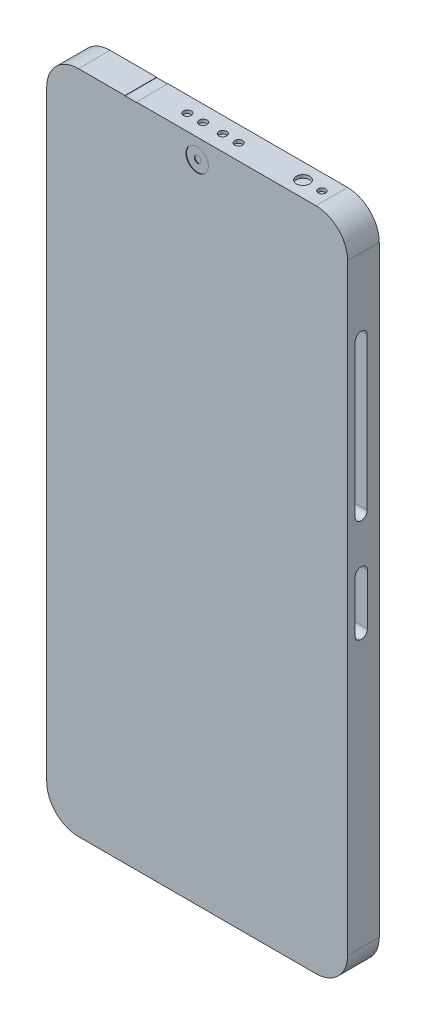
SolidWorks part; units mm, degrees
material "C (石墨)"
ref_plane "前视基准面" through (0, 0, 0) normal (0, 0, 1) x (1, 0, 0)
ref_plane "上视基准面" through (0, 0, 0) normal (0, 1, 0) x (1, 0, 0)
ref_plane "右视基准面" through (0, 0, 0) normal (1, 0, 0) x (0, 0, -1)
other "Configuration Table"
sketch "草图1" plane through (0, 0, 0) normal (0, 0, 1) x (1, 0, 0)
  line L1 (-37.5, 105) -> (37.5, 105)
  line L2 (-47.5, 95) -> (-47.5, -95)
  line L3 (-37.5, -105) -> (37.5, -105)
  line L4 (47.5, 95) -> (47.5, -95)
  line L5 (-47.5, 105) -> (47.5, -105) construction
  line L6 (-47.5, -105) -> (47.5, 105) construction
  arc A0 (-37.5, 105) -> (-47.5, 95) centre (-37.5, 95) ccw
  arc A1 (47.5, 95) -> (37.5, 105) centre (37.5, 95) ccw
  arc A2 (47.5, -95) -> (37.5, -105) centre (37.5, -95) cw
  arc A3 (-37.5, -105) -> (-47.5, -95) centre (-37.5, -95) cw
  point P0 (0, 0)
  dimension "D3" = 10
  dimension "D4" = 10
  dimension "D5" = 10
  dimension "D1" = 95
  dimension "D2" = 210
extrude "凸台-拉伸2" add sketch "草图1" along normal blind 10 contours A0 L2 A3 L3 A2 L4 A1 L1
sketch "草图8" plane through (0, 105, 0) normal (0, 1, 0) x (1, 0, 0)
  line L0 (0, -10) -> (0, 0) construction
  line L1 (-37.5, -10) -> (37.5, -10) construction
  line L3 (-37.5, 0) -> (37.5, 0) construction
  line L5 (-22.7874, 0) -> (-19.2126, 0)
  line L6 (-22.7874, 0) -> (-22.7874, -10)
  line L7 (-22.7874, -10) -> (-19.2126, -10)
  line L8 (-19.2126, 0) -> (-19.2126, -10)
  line L9 (22.7874, -10) -> (19.2126, -10)
  line L10 (19.2126, 0) -> (19.2126, -10)
  line L11 (22.7874, 0) -> (19.2126, 0)
  line L12 (22.7874, 0) -> (22.7874, -10)
  dimension "D2" = 42
  dimension "D1" = 3.5748
sketch "草图10" plane through (0, 105, 0) normal (0, 1, 0) x (1, 0, 0)
  line L0 (-37.5, -5) -> (37.5, -5) construction
  line L4 (0, 0) -> (0, -10) construction
  circle A0 centre (-3.1032, -5) radius 1.25
  circle A1 centre (-8.1032, -5) radius 1.25
  circle A2 centre (8.1032, -5) radius 1.25
  circle A3 centre (3.1032, -5) radius 1.25
  circle A4 centre (28.4294, -5) radius 2.1
  circle A5 centre (34.3689, -5) radius 1.15
  dimension "D2" = 2.5
  dimension "D3" = 4.2
  dimension "D4" = 2.3
  dimension "D1" = 2
sketch "草图12" plane through (0, 105, 0) normal (0, 1, 0) x (1, 0, 0)
extrude "切除-拉伸3" cut sketch "草图10" against normal blind 1 contours A4 | A2 | A3 | A0 | A1 | A5
sketch "草图14" plane through (0, -105, 0) normal (0, -1, 0) x (1, 0, 0)
  line L0 (-4.965, 4.9007) -> (4.835, 4.9007) construction
  line L1 (-4.965, 8.2769) -> (4.835, 8.2769)
  line L2 (-4.965, 1.5245) -> (4.835, 1.5245)
  arc A0 (-4.965, 8.2769) -> (-4.965, 1.5245) centre (-4.965, 4.9007) ccw
  arc A1 (4.835, 1.5245) -> (4.835, 8.2769) centre (4.835, 4.9007) ccw
  point P2 (-0.065, 4.9007)
  dimension "D1" = 3.3762
  dimension "D2" = 9.8
sketch "草图15" plane through (0, -105, 0) normal (0, -1, 0) x (1, 0, 0)
extrude "切除-拉伸4" cut sketch "草图14" against normal blind 20.0858 contours L2 A1 L1 A0
sketch "草图16" plane through (0, -105, 0) normal (0, -1, 0) x (1, 0, 0)
  line L0 (-35.02, 5.1655) -> (-20.02, 5.1655) construction
  line L1 (-35.02, 6.9529) -> (-20.02, 6.9529)
  line L2 (-35.02, 3.3781) -> (-20.02, 3.3781)
  arc A0 (-35.02, 6.9529) -> (-35.02, 3.3781) centre (-35.02, 5.1655) ccw
  arc A1 (-20.02, 3.3781) -> (-20.02, 6.9529) centre (-20.02, 5.1655) ccw
  circle A2 centre (-35.02, 5.1655) radius 0.55
  circle A3 centre (-14.9073, 5.1655) radius 1.45
  circle A4 centre (14.7296, 5.1655) radius 2.3283
  circle A5 centre (19.7296, 5.1655) radius 2.3283
  circle A6 centre (24.7296, 5.1655) radius 2.3283
  circle A7 centre (29.7296, 5.1655) radius 2.3283
  circle A8 centre (34.7296, 5.1655) radius 2.3283
  point P2 (-27.52, 5.1655)
  point P13 (-18.2326, 5.1655)
  dimension "D1" = 2.9
  dimension "D3" = 1.1
  dimension "D5" = 4.6566
  dimension "D2" = 15
  dimension "D6" = 3.3252
  dimension "D7" = 5
  dimension "D8" = 29.6369
  dimension "D4" = 5
extrude "切除-拉伸6" cut sketch "草图16" against normal blind 10 contours A4 | A3 | A8 | A7 | A6 | A5
sketch "草图18" plane through (0, -105, 0) normal (0, -1, 0) x (1, 0, 0)
  line L0 (-34.9782, 4.8823) -> (-19.8978, 4.8823) construction
  line L1 (-34.9782, 6.9263) -> (-19.8978, 6.9263)
  line L2 (-34.9782, 2.8383) -> (-19.8978, 2.8383)
  arc A0 (-34.9782, 6.9263) -> (-34.9782, 2.8383) centre (-34.9782, 4.8823) ccw
  arc A1 (-19.8978, 2.8383) -> (-19.8978, 6.9263) centre (-19.8978, 4.8823) ccw
  circle A2 centre (-34.9782, 4.8823) radius 0.5451
  point P2 (-27.438, 4.8823)
extrude "切除-拉伸7" cut sketch "草图18" against normal blind 10 contours A2
sketch "草图19" plane through (0, -105, 0) normal (0, -1, 0) x (1, 0, 0)
  line L0 (-34.9782, 4.8823) -> (-21.8321, 4.8823) construction
  line L1 (-34.9782, 7.0648) -> (-21.8321, 7.0648)
  line L2 (-34.9782, 2.6998) -> (-21.8321, 2.6998)
  arc A0 (-34.9782, 7.0648) -> (-34.9782, 2.6998) centre (-34.9782, 4.8823) ccw
  arc A1 (-21.8321, 2.6998) -> (-21.8321, 7.0648) centre (-21.8321, 4.8823) ccw
  point P3 (-28.4052, 4.8823)
sketch "草图21" plane through (47.5, 0, 0) normal (1, 0, 0) x (0, 0, -1)
  line L0 (-5.7088, 95) -> (-5.7088, 76.9914) construction
  line L1 (-5.7088, 71.612) -> (-5.7088, 23.612) construction
  line L2 (-3.8094, 71.612) -> (-3.8094, 23.612)
  line L3 (-7.6082, 71.612) -> (-7.6082, 23.612)
  line L4 (-5.7088, 7.2023) -> (-5.7088, -8.7873) construction
  line L5 (-3.7538, 7.2023) -> (-3.7538, -8.7873)
  line L6 (-7.6637, 7.2023) -> (-7.6637, -8.7873)
  arc A0 (-3.8094, 71.612) -> (-7.6082, 71.612) centre (-5.7088, 71.612) ccw
  arc A1 (-7.6082, 23.612) -> (-3.8094, 23.612) centre (-5.7088, 23.612) ccw
  arc A2 (-3.7538, 7.2023) -> (-7.6637, 7.2023) centre (-5.7088, 7.2023) ccw
  arc A3 (-7.6637, -8.7873) -> (-3.7538, -8.7873) centre (-5.7088, -8.7873) ccw
  point P3 (-5.7088, 47.612)
  point P11 (-5.7088, -0.7925)
  dimension "D3" = 1.9549
  dimension "D1" = 1.8994
  dimension "D2" = 48
  dimension "D4" = 15.9896
extrude "切除-拉伸8" cut sketch "草图21" against normal blind 8
sketch "草图22" plane through (0, 0, 10) normal (0, 0, 1) x (1, 0, 0)
  circle A0 centre (0, 98.826) radius 3.5506
extrude "切除-拉伸9" cut sketch "草图22" against normal blind 0.2
sketch "草图23" plane through (0, 0, 9.8) normal (0, 0, 1) x (1, 0, 0)
  circle A0 centre (0, 98.826) radius 1.0708
extrude "切除-拉伸10" cut sketch "草图23" against normal blind 0.2
extrude "切除-拉伸11" cut sketch "草图19" against normal blind 0.1 contours L1 A1 L2 A0
extrude "切除-拉伸13" cut sketch "草图8" against normal blind 0.1 contours L6 L7 L8 L5
